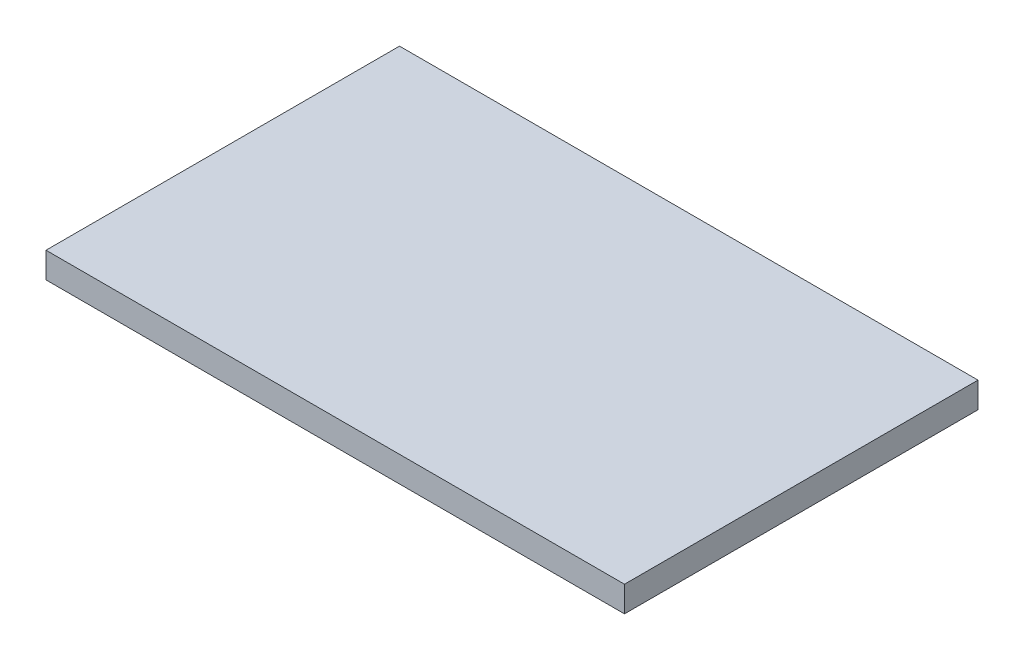
SolidWorks part; units mm, degrees
ref_plane "Спереди" through (0, 0, 0) normal (0, 0, 1) x (1, 0, 0)
ref_plane "Сверху" through (0, 0, 0) normal (0, 1, 0) x (1, 0, 0)
ref_plane "Справа" through (0, 0, 0) normal (1, 0, 0) x (0, 0, -1)
sketch "Эскиз1" plane through (0, 0, 0) normal (0, 1, 0) x (1, 0, 0)
  line L1 (45, -27.5) -> (-45, -27.5)
  line L2 (45, -27.5) -> (45, 27.5)
  line L3 (45, 27.5) -> (-45, 27.5)
  line L4 (-45, -27.5) -> (-45, 27.5)
  line L5 (45, -27.5) -> (-45, 27.5) construction
  line L6 (45, 27.5) -> (-45, -27.5) construction
  point P0 (0, 0)
extrude "Бобышка-Вытянуть1" add sketch "Эскиз1" along normal blind 4
